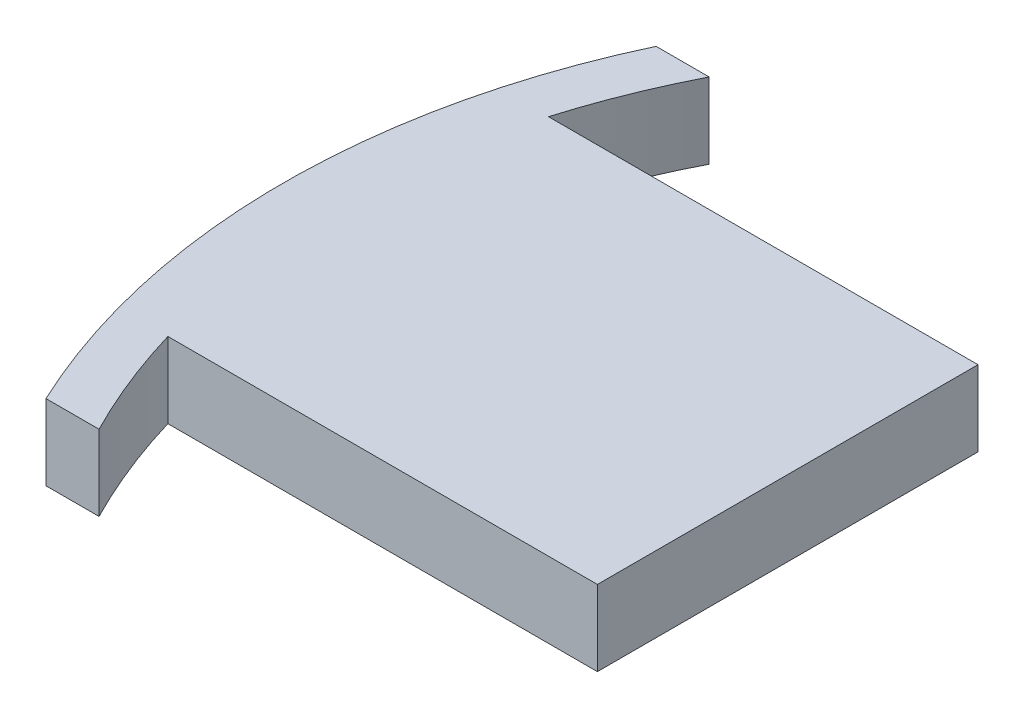
SolidWorks part; units mm, degrees
ref_plane "Front Plane" through (0, 0, 0) normal (0, 0, 1) x (1, 0, 0)
ref_plane "Top Plane" through (0, 0, 0) normal (0, 1, 0) x (1, 0, 0)
ref_plane "Right Plane" through (0, 0, 0) normal (1, 0, 0) x (0, 0, -1)
sketch "Sketch1" plane through (0, 0, 0) normal (0, 1, 0) x (1, 0, 0)
  line L0 (-17.505, 14.8783) -> (-17.505, -15.9242) construction
  line L1 (-17.505, 0) -> (-5.555, 0) construction
  line L2 (-18.0779, 4.975) -> (-5.555, 4.975)
  line L3 (-5.555, 4.975) -> (-5.555, 0)
  line L4 (-5.555, 0) -> (-5.555, -4.975)
  line L5 (-5.555, -4.975) -> (-18.0779, -4.975)
  line L6 (-16.9694, 7.975) -> (-15.5828, 7.975)
  line L7 (-15.5828, -7.975) -> (-16.9694, -7.975)
  circle A0 centre (0, 0) radius 17.505
  circle A1 centre (0, 0) radius 18.75
  dimension "D1" = 35.01
  dimension "D2" = 37.5
  dimension "D3" = 11.95
  dimension "D4" = 4.975
  dimension "D5" = 4.975
  dimension "D6" = 3
  dimension "D7" = 3
extrude "Boss-Extrude2" add sketch "Sketch1" along normal blind 1.975 contours L5 A1 L7 A0 | L2 A0 L5 L4 L3 | L2 A1 L5 A0 | L6 A1 L2 A0
